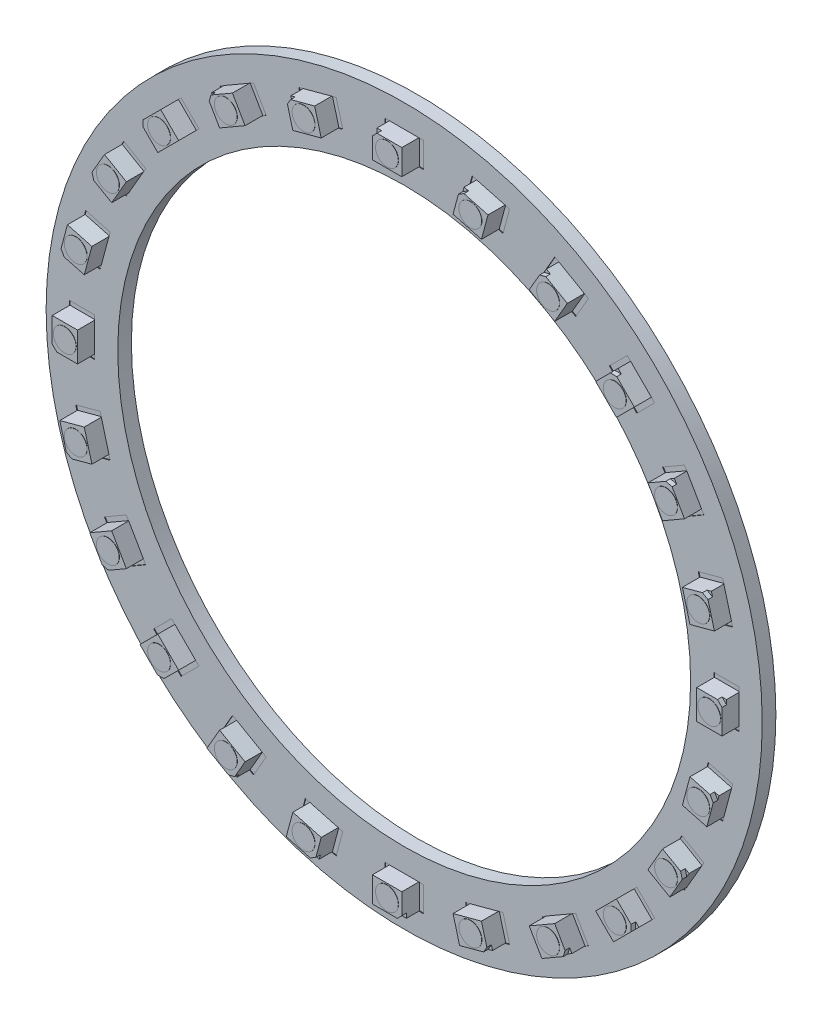
SolidWorks part; units mm, degrees
ref_plane "Front Plane" through (0, 0, 0) normal (0, 0, 1) x (1, 0, 0)
ref_plane "Top Plane" through (0, 0, 0) normal (0, 1, 0) x (1, 0, 0)
ref_plane "Right Plane" through (0, 0, 0) normal (1, 0, 0) x (0, 0, -1)
sketch "Sketch1" plane through (0, 0, 0) normal (0, 0, 1) x (1, 0, 0)
  circle A0 centre (0, 0) radius 39.9034
  circle A1 centre (0, 0) radius 31.9202
  dimension "D1" = 79.8068
  dimension "D2" = 7.9832
extrude "Boss-Extrude1" add sketch "Sketch1" along normal blind 1.52
sketch "Sketch2" plane through (0, 0, 1.52) normal (0, 0, 1) x (1, 0, 0)
  line L0 (0, 31.9202) -> (0, 39.9034) construction
  line L1 (-1.6383, 34.5021) -> (1.6383, 34.5021)
  line L2 (-1.6383, 34.5021) -> (-1.6383, 37.3215)
  line L3 (-1.6383, 37.3215) -> (1.6383, 37.3215)
  line L4 (1.6383, 34.5021) -> (1.6383, 37.3215)
  line L5 (-1.6383, 34.5021) -> (1.6383, 37.3215) construction
  line L6 (-1.6383, 37.3215) -> (1.6383, 34.5021) construction
  line L7 (7.3473, 33.7505) -> (10.5123, 32.9024)
  line L8 (7.3473, 33.7505) -> (8.077, 36.4738)
  line L9 (8.077, 36.4738) -> (11.242, 35.6258)
  line L10 (10.5123, 32.9024) -> (11.242, 35.6258)
  line L11 (7.3473, 33.7505) -> (11.242, 35.6258) construction
  line L12 (8.077, 36.4738) -> (10.5123, 32.9024) construction
  line L13 (15.8322, 30.6988) -> (18.6699, 29.0605)
  line L14 (15.8322, 30.6988) -> (17.2419, 33.1405)
  line L15 (17.2419, 33.1405) -> (20.0796, 31.5022)
  line L16 (18.6699, 29.0605) -> (20.0796, 31.5022)
  line L17 (15.8322, 30.6988) -> (20.0796, 31.5022) construction
  line L18 (17.2419, 33.1405) -> (18.6699, 29.0605) construction
  line L19 (23.2382, 25.5551) -> (25.5551, 23.2382)
  line L20 (23.2382, 25.5551) -> (25.2318, 27.5487)
  line L21 (25.2318, 27.5487) -> (27.5487, 25.2318)
  line L22 (25.5551, 23.2382) -> (27.5487, 25.2318)
  line L23 (23.2382, 25.5551) -> (27.5487, 25.2318) construction
  line L24 (25.2318, 27.5487) -> (25.5551, 23.2382) construction
  line L25 (29.0605, 18.6699) -> (30.6988, 15.8322)
  line L26 (29.0605, 18.6699) -> (31.5022, 20.0796)
  line L27 (31.5022, 20.0796) -> (33.1405, 17.2419)
  line L28 (30.6988, 15.8322) -> (33.1405, 17.2419)
  line L29 (29.0605, 18.6699) -> (33.1405, 17.2419) construction
  line L30 (31.5022, 20.0796) -> (30.6988, 15.8322) construction
  line L31 (32.9024, 10.5123) -> (33.7505, 7.3473)
  line L32 (32.9024, 10.5123) -> (35.6258, 11.242)
  line L33 (35.6258, 11.242) -> (36.4738, 8.077)
  line L34 (33.7505, 7.3473) -> (36.4738, 8.077)
  line L35 (32.9024, 10.5123) -> (36.4738, 8.077) construction
  line L36 (35.6258, 11.242) -> (33.7505, 7.3473) construction
  line L37 (34.5021, 1.6383) -> (34.5021, -1.6383)
  line L38 (34.5021, 1.6383) -> (37.3215, 1.6383)
  line L39 (37.3215, 1.6383) -> (37.3215, -1.6383)
  line L40 (34.5021, -1.6383) -> (37.3215, -1.6383)
  line L41 (34.5021, 1.6383) -> (37.3215, -1.6383) construction
  line L42 (37.3215, 1.6383) -> (34.5021, -1.6383) construction
  line L43 (33.7505, -7.3473) -> (32.9024, -10.5123)
  line L44 (33.7505, -7.3473) -> (36.4738, -8.077)
  line L45 (36.4738, -8.077) -> (35.6258, -11.242)
  line L46 (32.9024, -10.5123) -> (35.6258, -11.242)
  line L47 (33.7505, -7.3473) -> (35.6258, -11.242) construction
  line L48 (36.4738, -8.077) -> (32.9024, -10.5123) construction
  line L49 (30.6988, -15.8322) -> (29.0605, -18.6699)
  line L50 (30.6988, -15.8322) -> (33.1405, -17.2419)
  line L51 (33.1405, -17.2419) -> (31.5022, -20.0796)
  line L52 (29.0605, -18.6699) -> (31.5022, -20.0796)
  line L53 (30.6988, -15.8322) -> (31.5022, -20.0796) construction
  line L54 (33.1405, -17.2419) -> (29.0605, -18.6699) construction
  line L55 (25.5551, -23.2382) -> (23.2382, -25.5551)
  line L56 (25.5551, -23.2382) -> (27.5487, -25.2318)
  line L57 (27.5487, -25.2318) -> (25.2318, -27.5487)
  line L58 (23.2382, -25.5551) -> (25.2318, -27.5487)
  line L59 (25.5551, -23.2382) -> (25.2318, -27.5487) construction
  line L60 (27.5487, -25.2318) -> (23.2382, -25.5551) construction
  line L61 (18.6699, -29.0605) -> (15.8322, -30.6988)
  line L62 (18.6699, -29.0605) -> (20.0796, -31.5022)
  line L63 (20.0796, -31.5022) -> (17.2419, -33.1405)
  line L64 (15.8322, -30.6988) -> (17.2419, -33.1405)
  line L65 (18.6699, -29.0605) -> (17.2419, -33.1405) construction
  line L66 (20.0796, -31.5022) -> (15.8322, -30.6988) construction
  line L67 (10.5123, -32.9024) -> (7.3473, -33.7505)
  line L68 (10.5123, -32.9024) -> (11.242, -35.6258)
  line L69 (11.242, -35.6258) -> (8.077, -36.4738)
  line L70 (7.3473, -33.7505) -> (8.077, -36.4738)
  line L71 (10.5123, -32.9024) -> (8.077, -36.4738) construction
  line L72 (11.242, -35.6258) -> (7.3473, -33.7505) construction
  line L73 (1.6383, -34.5021) -> (-1.6383, -34.5021)
  line L74 (1.6383, -34.5021) -> (1.6383, -37.3215)
  line L75 (1.6383, -37.3215) -> (-1.6383, -37.3215)
  line L76 (-1.6383, -34.5021) -> (-1.6383, -37.3215)
  line L77 (1.6383, -34.5021) -> (-1.6383, -37.3215) construction
  line L78 (1.6383, -37.3215) -> (-1.6383, -34.5021) construction
  line L79 (-7.3473, -33.7505) -> (-10.5123, -32.9024)
  line L80 (-7.3473, -33.7505) -> (-8.077, -36.4738)
  line L81 (-8.077, -36.4738) -> (-11.242, -35.6258)
  line L82 (-10.5123, -32.9024) -> (-11.242, -35.6258)
  line L83 (-7.3473, -33.7505) -> (-11.242, -35.6258) construction
  line L84 (-8.077, -36.4738) -> (-10.5123, -32.9024) construction
  line L85 (-15.8322, -30.6988) -> (-18.6699, -29.0605)
  line L86 (-15.8322, -30.6988) -> (-17.2419, -33.1405)
  line L87 (-17.2419, -33.1405) -> (-20.0796, -31.5022)
  line L88 (-18.6699, -29.0605) -> (-20.0796, -31.5022)
  line L89 (-15.8322, -30.6988) -> (-20.0796, -31.5022) construction
  line L90 (-17.2419, -33.1405) -> (-18.6699, -29.0605) construction
  line L91 (-23.2382, -25.5551) -> (-25.5551, -23.2382)
  line L92 (-23.2382, -25.5551) -> (-25.2318, -27.5487)
  line L93 (-25.2318, -27.5487) -> (-27.5487, -25.2318)
  line L94 (-25.5551, -23.2382) -> (-27.5487, -25.2318)
  line L95 (-23.2382, -25.5551) -> (-27.5487, -25.2318) construction
  line L96 (-25.2318, -27.5487) -> (-25.5551, -23.2382) construction
  line L97 (-29.0605, -18.6699) -> (-30.6988, -15.8322)
  line L98 (-29.0605, -18.6699) -> (-31.5022, -20.0796)
  line L99 (-31.5022, -20.0796) -> (-33.1405, -17.2419)
  line L100 (-30.6988, -15.8322) -> (-33.1405, -17.2419)
  line L101 (-29.0605, -18.6699) -> (-33.1405, -17.2419) construction
  line L102 (-31.5022, -20.0796) -> (-30.6988, -15.8322) construction
  line L103 (-32.9024, -10.5123) -> (-33.7505, -7.3473)
  line L104 (-32.9024, -10.5123) -> (-35.6258, -11.242)
  line L105 (-35.6258, -11.242) -> (-36.4738, -8.077)
  line L106 (-33.7505, -7.3473) -> (-36.4738, -8.077)
  line L107 (-32.9024, -10.5123) -> (-36.4738, -8.077) construction
  line L108 (-35.6258, -11.242) -> (-33.7505, -7.3473) construction
  line L109 (-34.5021, -1.6383) -> (-34.5021, 1.6383)
  line L110 (-34.5021, -1.6383) -> (-37.3215, -1.6383)
  line L111 (-37.3215, -1.6383) -> (-37.3215, 1.6383)
  line L112 (-34.5021, 1.6383) -> (-37.3215, 1.6383)
  line L113 (-34.5021, -1.6383) -> (-37.3215, 1.6383) construction
  line L114 (-37.3215, -1.6383) -> (-34.5021, 1.6383) construction
  line L115 (-33.7505, 7.3473) -> (-32.9024, 10.5123)
  line L116 (-33.7505, 7.3473) -> (-36.4738, 8.077)
  line L117 (-36.4738, 8.077) -> (-35.6258, 11.242)
  line L118 (-32.9024, 10.5123) -> (-35.6258, 11.242)
  line L119 (-33.7505, 7.3473) -> (-35.6258, 11.242) construction
  line L120 (-36.4738, 8.077) -> (-32.9024, 10.5123) construction
  line L121 (-30.6988, 15.8322) -> (-29.0605, 18.6699)
  line L122 (-30.6988, 15.8322) -> (-33.1405, 17.2419)
  line L123 (-33.1405, 17.2419) -> (-31.5022, 20.0796)
  line L124 (-29.0605, 18.6699) -> (-31.5022, 20.0796)
  line L125 (-30.6988, 15.8322) -> (-31.5022, 20.0796) construction
  line L126 (-33.1405, 17.2419) -> (-29.0605, 18.6699) construction
  line L127 (-25.5551, 23.2382) -> (-23.2382, 25.5551)
  line L128 (-25.5551, 23.2382) -> (-27.5487, 25.2318)
  line L129 (-27.5487, 25.2318) -> (-25.2318, 27.5487)
  line L130 (-23.2382, 25.5551) -> (-25.2318, 27.5487)
  line L131 (-25.5551, 23.2382) -> (-25.2318, 27.5487) construction
  line L132 (-27.5487, 25.2318) -> (-23.2382, 25.5551) construction
  line L133 (-18.6699, 29.0605) -> (-15.8322, 30.6988)
  line L134 (-18.6699, 29.0605) -> (-20.0796, 31.5022)
  line L135 (-20.0796, 31.5022) -> (-17.2419, 33.1405)
  line L136 (-15.8322, 30.6988) -> (-17.2419, 33.1405)
  line L137 (-18.6699, 29.0605) -> (-17.2419, 33.1405) construction
  line L138 (-20.0796, 31.5022) -> (-15.8322, 30.6988) construction
  line L139 (-10.5123, 32.9024) -> (-7.3473, 33.7505)
  line L140 (-10.5123, 32.9024) -> (-11.242, 35.6258)
  line L141 (-11.242, 35.6258) -> (-8.077, 36.4738)
  line L142 (-7.3473, 33.7505) -> (-8.077, 36.4738)
  line L143 (-10.5123, 32.9024) -> (-8.077, 36.4738) construction
  line L144 (-11.242, 35.6258) -> (-7.3473, 33.7505) construction
  circle A0 centre (0, 0) radius 31.9202 construction
  circle A1 centre (0, 0) radius 39.9034 construction
  circle A2 centre (0, 0) radius 35.9118 construction
  point P7 (0, 35.9118)
  point P11 (0, 35.9118)
  point P12 (0, 35.9118)
  point P20 (9.2947, 34.6881)
  point P21 (9.2947, 34.6881)
  point P22 (9.2947, 34.6881)
  point P27 (17.9559, 31.1005)
  point P28 (17.9559, 31.1005)
  point P29 (17.9559, 31.1005)
  point P34 (25.3935, 25.3935)
  point P35 (25.3935, 25.3935)
  point P36 (25.3935, 25.3935)
  point P41 (31.1005, 17.9559)
  point P42 (31.1005, 17.9559)
  point P43 (31.1005, 17.9559)
  point P48 (34.6881, 9.2947)
  point P49 (34.6881, 9.2947)
  point P50 (34.6881, 9.2947)
  point P55 (35.9118, 0)
  point P56 (35.9118, 0)
  point P57 (35.9118, 0)
  point P62 (34.6881, -9.2947)
  point P63 (34.6881, -9.2947)
  point P64 (34.6881, -9.2947)
  point P69 (31.1005, -17.9559)
  point P70 (31.1005, -17.9559)
  point P71 (31.1005, -17.9559)
  point P76 (25.3935, -25.3935)
  point P77 (25.3935, -25.3935)
  point P78 (25.3935, -25.3935)
  point P83 (17.9559, -31.1005)
  point P84 (17.9559, -31.1005)
  point P85 (17.9559, -31.1005)
  point P90 (9.2947, -34.6881)
  point P91 (9.2947, -34.6881)
  point P92 (9.2947, -34.6881)
  point P97 (0, -35.9118)
  point P98 (0, -35.9118)
  point P99 (0, -35.9118)
  point P104 (-9.2947, -34.6881)
  point P105 (-9.2947, -34.6881)
  point P106 (-9.2947, -34.6881)
  point P111 (-17.9559, -31.1005)
  point P112 (-17.9559, -31.1005)
  point P113 (-17.9559, -31.1005)
  point P118 (-25.3935, -25.3935)
  point P119 (-25.3935, -25.3935)
  point P120 (-25.3935, -25.3935)
  point P125 (-31.1005, -17.9559)
  point P126 (-31.1005, -17.9559)
  point P127 (-31.1005, -17.9559)
  point P132 (-34.6881, -9.2947)
  point P133 (-34.6881, -9.2947)
  point P134 (-34.6881, -9.2947)
  point P139 (-35.9118, 0)
  point P140 (-35.9118, 0)
  point P141 (-35.9118, 0)
  point P146 (-34.6881, 9.2947)
  point P147 (-34.6881, 9.2947)
  point P148 (-34.6881, 9.2947)
  point P153 (-31.1005, 17.9559)
  point P154 (-31.1005, 17.9559)
  point P155 (-31.1005, 17.9559)
  point P160 (-25.3935, 25.3935)
  point P161 (-25.3935, 25.3935)
  point P162 (-25.3935, 25.3935)
  point P167 (-17.9559, 31.1005)
  point P168 (-17.9559, 31.1005)
  point P169 (-17.9559, 31.1005)
  point P174 (-9.2947, 34.6881)
  point P175 (-9.2947, 34.6881)
  point P176 (-9.2947, 34.6881)
  point P181 (0, 0)
  dimension "D1" = 2.8194
  dimension "D2" = 3.2766
  dimension "D3" = 24
extrude "Boss-Extrude2" add sketch "Sketch2" along normal blind 1.9
sketch "Sketch3" plane through (0, 0, 3.42) normal (0, 0, 1) x (1, 0, 0)
  line L0 (9.6595, 36.0498) -> (8.9298, 33.3265) construction
  line L1 (11.242, 35.6258) -> (8.077, 36.4738) construction
  line L2 (7.3473, 33.7505) -> (10.5123, 32.9024) construction
  circle A0 centre (9.2947, 34.6881) radius 1.27
  dimension "D1" = 2.54
extrude "Boss-Extrude3" add sketch "Sketch3" along normal blind 0.0254
pattern_circular "CirPattern1" count 24 over 360 about axis through (0, 0, 0) along (0, 0, 1) of "Boss-Extrude3"
sketch "Sketch4" plane through (0, 0, 3.42) normal (0, 0, 1) x (1, 0, 0)
  line L0 (-1.6383, 36.8135) -> (-1.1303, 37.3215)
  line L1 (-1.1303, 37.3215) -> (-1.6383, 37.3215)
  line L2 (-1.6383, 37.3215) -> (-1.6383, 36.8135)
  point P3 (-1.6383, 37.3215)
  dimension "D1" = 0.508
  dimension "D2" = 0.508
extrude "Cut-Extrude1" cut sketch "Sketch4" against normal blind 0.508
pattern_circular "CirPattern2" count 24 over 360 about axis through (0, 0, 0) along (0, 0, 1) of "Cut-Extrude1"
sketch "Sketch5" plane through (0, 0, 1.52) normal (0, 0, 1) x (1, 0, 0)
  line L0 (1.6383, 37.3215) -> (2.159, 37.3215)
  line L1 (-1.6383, 37.3215) -> (-1.6383, 34.5021)
  line L2 (-2.159, 34.5021) -> (-1.6383, 34.5021)
  line L3 (-2.159, 34.5021) -> (-2.159, 37.3215)
  line L4 (-2.159, 37.3215) -> (-1.6383, 37.3215)
  line L5 (2.159, 34.5021) -> (2.159, 37.3215)
  line L6 (1.6383, 34.5021) -> (2.159, 34.5021)
  line L7 (1.6383, 34.5021) -> (1.6383, 37.3215)
  point P0 (-1.6383, 37.3215)
  point P1 (0, 37.5958)
  dimension "D1" = 4.318
extrude "Cut-Extrude2" cut sketch "Sketch5" against normal blind 0.0762
pattern_circular "CirPattern3" count 24 over 360 about axis through (0, 0, 0) along (0, 0, 1) of "Cut-Extrude2"
